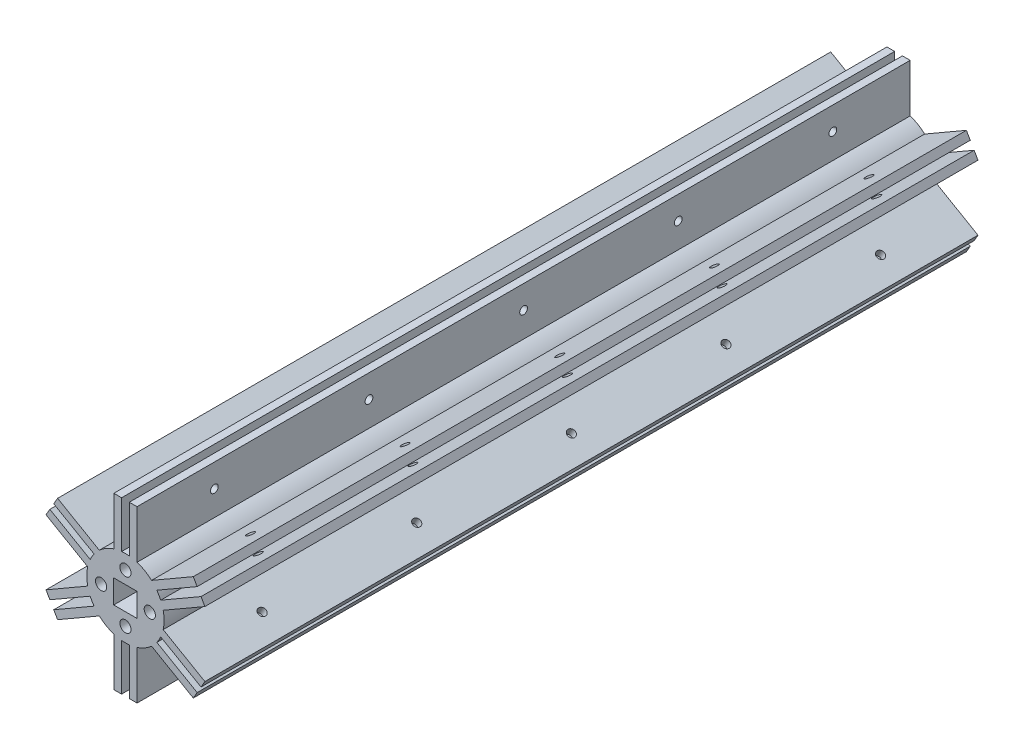
SolidWorks part; units mm, degrees
ref_plane "Front Plane" through (0, 0, 0) normal (0, 0, 1) x (1, 0, 0)
ref_plane "Top Plane" through (0, 0, 0) normal (0, 1, 0) x (1, 0, 0)
ref_plane "Right Plane" through (0, 0, 0) normal (1, 0, 0) x (0, 0, -1)
sketch "Sketch1" plane through (0, 0, 0) normal (0, 0, 1) x (1, 0, 0)
  circle A0 centre (0, 0) radius 10
  dimension "D2" = 20
extrude "Boss-Extrude1" add sketch "Sketch1" along normal mid plane 200
sketch "Sketch4" plane through (0, 0, 100) normal (0, 0, 1) x (1, 0, 0)
  line L0 (18.7973, 0) -> (-18.7973, 0) construction
  line L2 (-3, 0) -> (-1, 0)
  line L3 (0, 0) -> (0, 15.8331) construction
  line L4 (-3, 0) -> (-3, 22)
  line L5 (-3, 22) -> (-1, 22)
  line L6 (-1, 0) -> (-1, 22)
  line L7 (0, -19.8) -> (0, 19.8) construction
  line L8 (3, 22) -> (1, 22)
  line L9 (1, 0) -> (1, 22)
  line L10 (3, 0) -> (1, 0)
  line L11 (3, 0) -> (3, 22)
  dimension "D1" = 22
  dimension "D3" = 1
extrude "Boss-Extrude3" add sketch "Sketch4" against normal up to surface (200 mm away) up to face at (10, 0, -100)
pattern_circular "CirPattern7" count 6 over 360 about axis through (0, 0, 0) along (0, 0, 1) of "Boss-Extrude3"
sketch "Sketch7" plane through (-3, 0, 0) normal (-1, 0, 0) x (0, 0, 1)
  line L0 (-100, 22) -> (100, 22) construction
  line L1 (-100, 9.5394) -> (-100, 22) construction
  circle A0 centre (-80, 16) radius 1
  circle A1 centre (-40, 16) radius 1
  circle A2 centre (0, 16) radius 1
  circle A3 centre (40, 16) radius 1
  circle A4 centre (80, 16) radius 1
  dimension "D1" = 2
  dimension "D2" = 6
  dimension "D3" = 20
  dimension "D4" = 5
extrude "Cut-Extrude2" cut sketch "Sketch7" against normal blind 10
pattern_circular "CirPattern9" count 6 over 360 about axis through (0, 0, 100) along (0, 0, 1) of "Cut-Extrude2"
sketch "Sketch8" plane through (0, 0, 100) normal (0, 0, 1) x (1, 0, 0)
  line L2 (-3.0375, 3.0375) -> (3.0375, 3.0375)
  line L3 (-3.0375, 3.0375) -> (-3.0375, -3.0375)
  line L4 (-3.0375, -3.0375) -> (3.0375, -3.0375)
  line L5 (3.0375, 3.0375) -> (3.0375, -3.0375)
  line L6 (-3.0375, 3.0375) -> (3.0375, -3.0375) construction
  line L7 (-3.0375, -3.0375) -> (3.0375, 3.0375) construction
  point P5 (0, 0)
  point P14 (0, 0)
  dimension "D4" = 6.075
  dimension "D5" = 6.075
extrude "Cut-Extrude3" cut sketch "Sketch8" against normal up to next
sketch "Sketch9" plane through (0, 0, 100) normal (0, 0, 1) x (1, 0, 0)
  line L0 (18.7973, 0) -> (-18.7973, 0) construction
  circle A0 centre (6.3, 0) radius 1.45
  circle A1 centre (0, -6.3) radius 1.45
  circle A2 centre (-6.3, 0) radius 1.45
  circle A3 centre (0, 6.3) radius 1.45
  point P14 (0, 0)
  dimension "D1" = 2.9
  dimension "D2" = 6.3
  dimension "D3" = 4
extrude "Cut-Extrude4" cut sketch "Sketch9" against normal blind 10
equation "\"drumDiameter\"= 20mm"
equation "\"D2@Sketch1\"=\"drumDiameter\""
equation "\"drumLength\"= 200mm"
equation "\"D1@Sketch4\"=\"drumDiameter\"*(0.5+\"drumAbove\")"
equation "\"foamThickness\"= 2"
equation "\"D3@Sketch4\"=\"foamThickness\"/2"
equation "\"drumAbove\"= 0.6"
equation "\"D2@Sketch7\"=\"drumDiameter\"*\"drumAbove\"/2"
equation "\"holderThicc\"= 2"
equation "\"D2@Sketch4\"=\"holderThicc\""
equation "\"D5@Sketch8\"=12.15/2"
